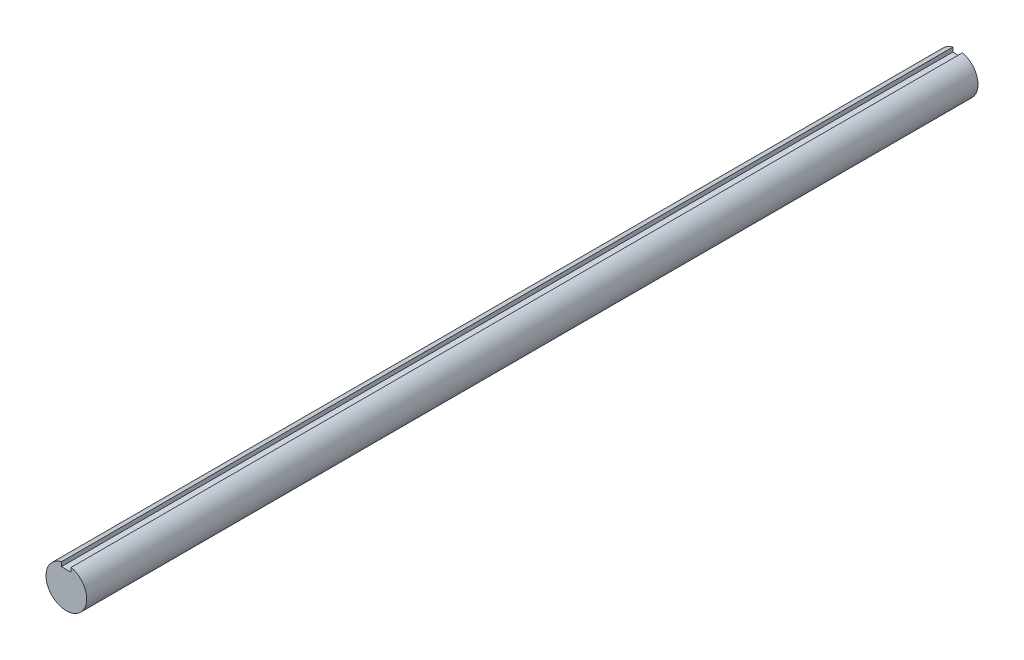
SolidWorks part; units mm, degrees
material "Cast Alloy Steel"
ref_plane "Front Plane" through (0, 0, 0) normal (0, 0, 1) x (1, 0, 0)
ref_plane "Top Plane" through (0, 0, 0) normal (0, 1, 0) x (1, 0, 0)
ref_plane "Right Plane" through (0, 0, 0) normal (1, 0, 0) x (0, 0, -1)
sketch "Sketch1" plane through (0, 0, 0) normal (0, 0, 1) x (1, 0, 0)
  line L0 (1.905, 7.7055) -> (1.905, 6.0325)
  line L1 (1.905, 6.0325) -> (-1.905, 6.0325)
  line L2 (-1.905, 6.0325) -> (-1.905, 7.7055)
  line L3 (0, 0) -> (0, 6.0325) construction
  arc A0 (-1.905, 7.7055) -> (1.905, 7.7055) centre (0, 0) ccw
  dimension "D1" = 7.9375
  dimension "D2" = 6.0325
  dimension "D3" = 3.81
extrude "Extrude1" add sketch "Sketch1" along normal mid plane 347.9267
